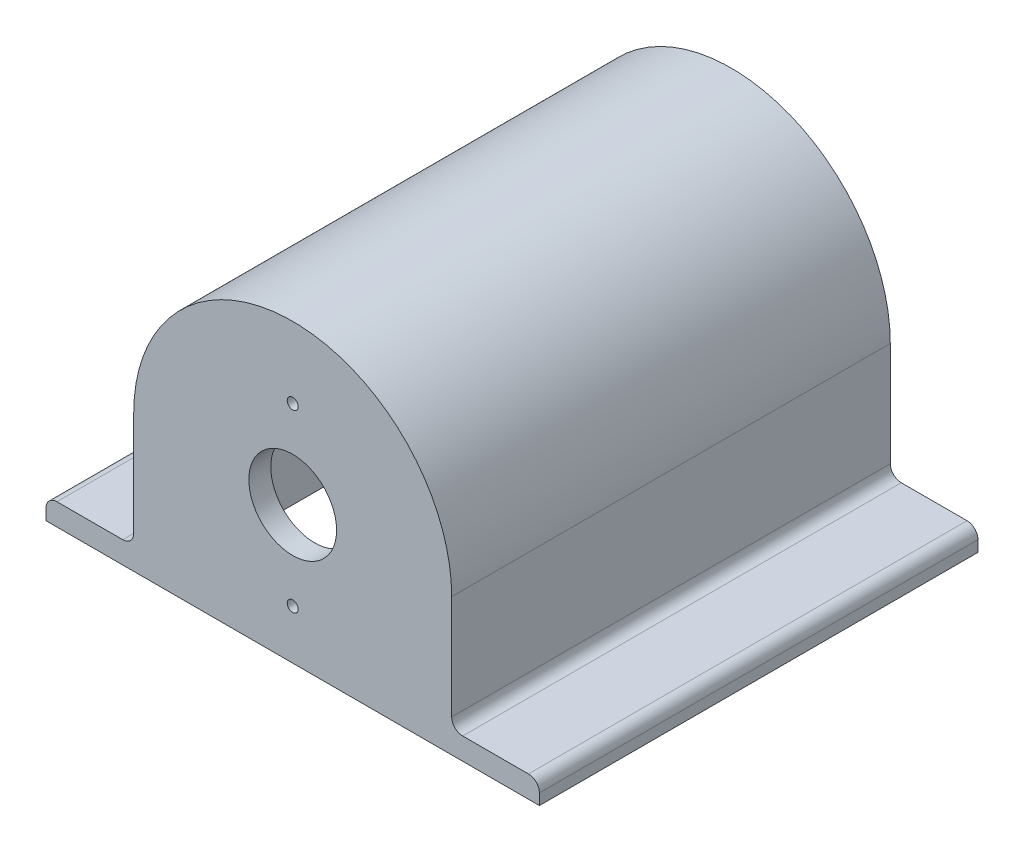
SolidWorks part; units mm, degrees
ref_plane "Plan de face" through (0, 0, 0) normal (0, 0, 1) x (1, 0, 0)
ref_plane "Plan de dessus" through (0, 0, 0) normal (0, 1, 0) x (1, 0, 0)
ref_plane "Plan de droite" through (0, 0, 0) normal (1, 0, 0) x (0, 0, -1)
sketch "Esquisse1" plane through (0, 0, 0) normal (0, 0, 1) x (1, 0, 0)
  line L0 (-14.5, 0) -> (14.5, 0)
  circle A0 centre (0, 0) radius 12.5
  circle A1 centre (0, 0) radius 14.5
  dimension "D1" = 25
  dimension "D2" = 29
extrude "Boss.-Extru.1" add sketch "Esquisse1" along normal blind 40 contours L0 A1 A0
sketch "Esquisse2" plane through (0, 0, 0) normal (0, -1, 0) x (1, 0, 0)
  line L1 (-14.5, 40) -> (-12.5, 40)
  line L2 (-14.5, 40) -> (-14.5, 0)
  line L3 (-14.5, 0) -> (-12.5, 0)
  line L4 (-12.5, 40) -> (-12.5, 0)
  line L5 (14.5, 0) -> (12.5, 0)
  line L6 (14.5, 0) -> (14.5, 40)
  line L7 (14.5, 40) -> (12.5, 40)
  line L8 (12.5, 0) -> (12.5, 40)
extrude "Boss.-Extru.2" add sketch "Esquisse2" along normal blind 12.5
sketch "Esquisse3" plane through (0, -12.5, 0) normal (0, -1, 0) x (1, 0, 0)
  line L1 (-12.5, 40) -> (-22.5, 40)
  line L2 (-12.5, 40) -> (-12.5, 0)
  line L3 (-12.5, 0) -> (-22.5, 0)
  line L4 (-22.5, 40) -> (-22.5, 0)
  line L5 (12.5, 40) -> (22.5, 40)
  line L6 (12.5, 40) -> (12.5, 0)
  line L7 (12.5, 0) -> (22.5, 0)
  line L8 (22.5, 40) -> (22.5, 0)
  dimension "D1" = 40
  dimension "D2" = 40
  dimension "D3" = 10
  dimension "D4" = 10
extrude "Boss.-Extru.3" add sketch "Esquisse3" against normal blind 2
sketch "Esquisse4" plane through (0, 0, 40) normal (0, 0, 1) x (1, 0, 0)
  line L1 (-12.5, -12.5) -> (12.5, -12.5)
  line L2 (-12.5, -12.5) -> (-12.5, 0)
  line L3 (-12.5, 0) -> (12.5, 0)
  line L4 (12.5, -12.5) -> (12.5, 0)
  circle A0 centre (0, 0) radius 12.5
  circle A1 centre (0, 0) radius 4
  line M8 (-12.5, -12.5) -> (-12.5, 0)
  arc M9 (-12.5, 0) -> (12.5, 0) centre (0, 0) cw
  line M10 (12.5, 0) -> (12.5, -12.5)
  dimension "D1" = 8
  dimension "D2" = 25
extrude "Boss.-Extru.4" add sketch "Esquisse4" against normal blind 2 contours A1 L3 M9 | A1 L3 A0 | A0 L1 M8 | A0 L1 M10
fillet "Congé1" radius 1 4 edges at (-22.5, -10.5, 20) (-14.5, -10.5, 20) (22.5, -10.5, 20) (14.5, -10.5, 20)
sketch "Esquisse5" plane through (0, 0, 40) normal (0, 0, 1) x (1, 0, 0)
  line L0 (0, -8) -> (0, 8)
  circle A0 centre (0, 0) radius 8
  circle A1 centre (0, -8) radius 0.5
  circle A2 centre (0, 8) radius 0.5
  dimension "D1" = 16
  dimension "D2" = 1
  dimension "D3" = 1
extrude "Enlèv. mat.-Extru.1" cut sketch "Esquisse5" against normal through all contours A2 | A1
